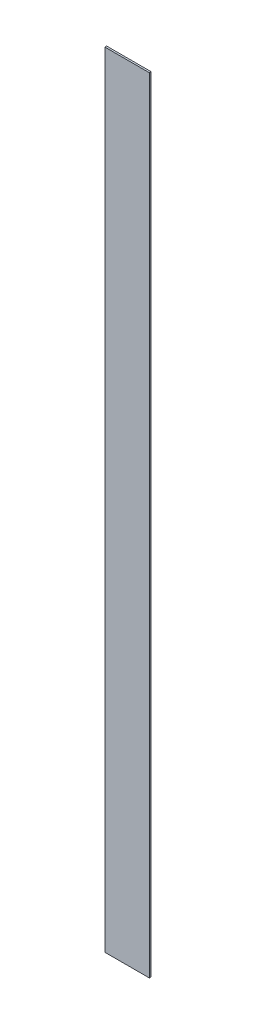
SolidWorks part; units mm, degrees
material "Силикон"
ref_plane "Спереди" through (0, 0, 0) normal (0, 0, 1) x (1, 0, 0)
ref_plane "Сверху" through (0, 0, 0) normal (0, 1, 0) x (1, 0, 0)
ref_plane "Справа" through (0, 0, 0) normal (1, 0, 0) x (0, 0, -1)
sketch "Эскиз1" plane through (0, 0, 0) normal (0, 0, 1) x (1, 0, 0)
  line L1 (-25, 440) -> (25, 440)
  line L2 (-25, 440) -> (-25, -440)
  line L3 (-25, -440) -> (25, -440)
  line L4 (25, 440) -> (25, -440)
  line L5 (-25, 440) -> (25, -440) construction
  line L6 (-25, -440) -> (25, 440) construction
  point P0 (0, 0)
  dimension "D1" = 50
  dimension "D2" = 880
extrude "Бобышка-Вытянуть1" add sketch "Эскиз1" along normal mid plane 2
